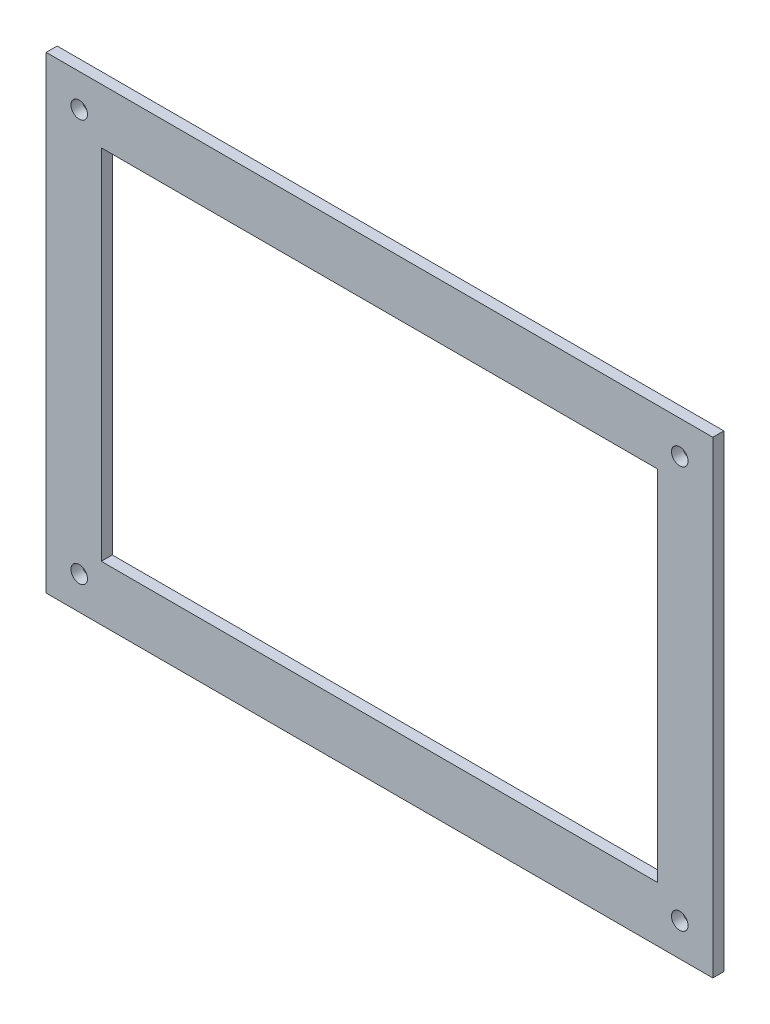
SolidWorks part; units mm, degrees
ref_plane "Ön Düzlem" through (0, 0, 0) normal (0, 0, 1) x (1, 0, 0)
ref_plane "Üst Düzlem" through (0, 0, 0) normal (0, 1, 0) x (1, 0, 0)
ref_plane "Sağ Düzlem" through (0, 0, 0) normal (1, 0, 0) x (0, 0, -1)
sketch "Sketch1" plane through (0, 0, 0) normal (0, 0, 1) x (1, 0, 0)
  line L1 (0, 0) -> (121, 0)
  line L2 (0, 0) -> (0, 85)
  line L3 (0, 85) -> (121, 85)
  line L4 (121, 0) -> (121, 85)
extrude "Boss-Extrude1" add sketch "Sketch1" along normal blind 2
sketch "Sketch4" plane through (0, 0, 2) normal (0, 0, 1) x (1, 0, 0)
  line L0 (0, 85) -> (0, 0) construction
  line L1 (10, 10) -> (111, 10)
  line L2 (10, 10) -> (10, 75)
  line L3 (10, 75) -> (111, 75)
  line L4 (111, 10) -> (111, 75)
  line L5 (0, 0) -> (121, 0) construction
  dimension "D1" = 10
  dimension "D2" = 10
extrude "Cut-Extrude1" cut sketch "Sketch4" against normal through all
sketch "Sketch5" plane through (0, 0, 2) normal (0, 0, 1) x (1, 0, 0)
  line L0 (0, 85) -> (0, 0) construction
  line L1 (121, 85) -> (0, 85) construction
  line L2 (121, 0) -> (121, 85) construction
  line L3 (0, 0) -> (121, 0) construction
  circle A0 centre (6, 79) radius 1.5
  circle A1 centre (115, 79) radius 1.5
  circle A2 centre (6, 6) radius 1.5
  circle A3 centre (115, 6) radius 1.5
  dimension "D1" = 6
  dimension "D3" = 6
  dimension "D5" = 6
  dimension "D2" = 6
  dimension "D4" = 6
extrude "Cut-Extrude2" cut sketch "Sketch5" against normal through all
